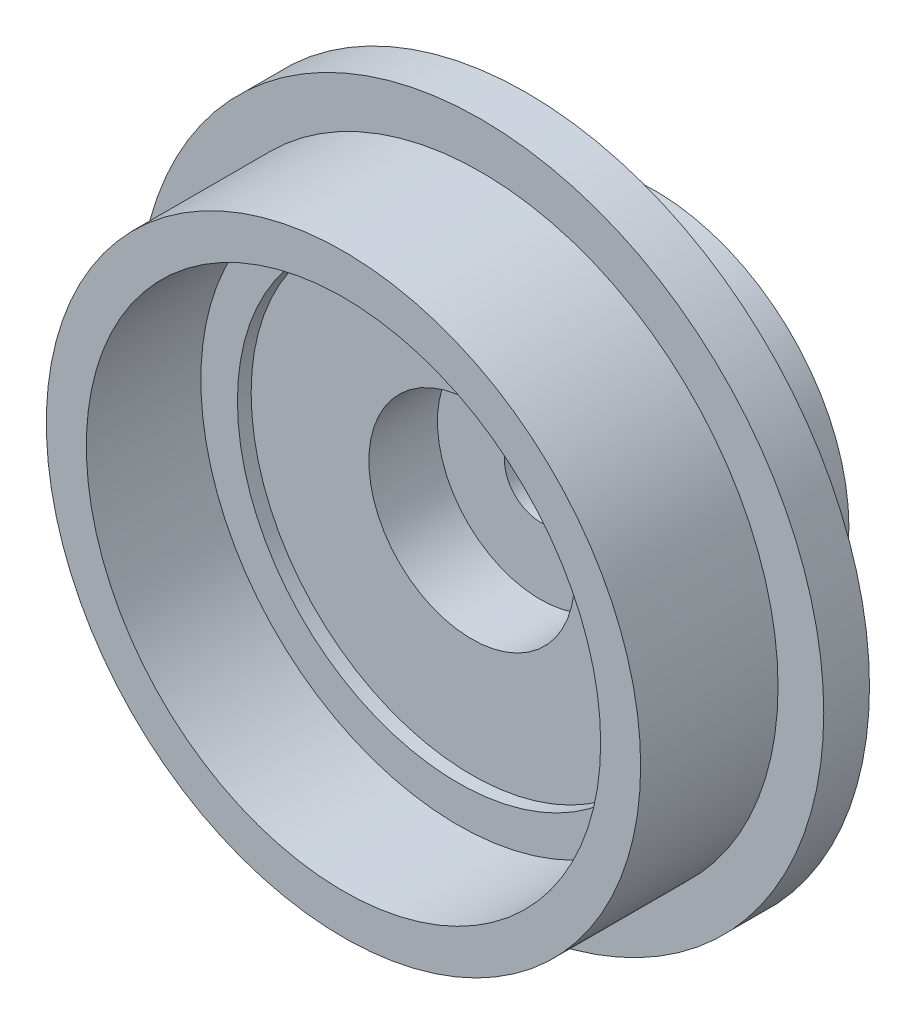
SolidWorks part; units mm, degrees
material "6061-T6 (SS)"
ref_plane "Front Plane" through (0, 0, 0) normal (0, 0, 1) x (1, 0, 0)
ref_plane "Top Plane" through (0, 0, 0) normal (0, 1, 0) x (1, 0, 0)
ref_plane "Right Plane" through (0, 0, 0) normal (1, 0, 0) x (0, 0, -1)
sketch "Sketch1" plane through (0, 0, 0) normal (1, 0, 0) x (0, 0, -1)
  line L0 (-32.3517, 0) -> (72.8588, 0) construction
  line L1 (17.2847, 0) -> (7.1247, 0)
  line L2 (7.1247, 0) -> (7.1247, 12.2555)
  line L3 (7.1247, 12.2555) -> (6.3627, 12.2555)
  line L4 (6.3627, 12.2555) -> (6.3627, 14.2875)
  line L5 (6.3627, 14.2875) -> (0, 14.2875)
  line L6 (0, 14.2875) -> (0, 16.51)
  line L7 (0, 16.51) -> (7.6327, 16.51)
  line L8 (10.1727, 19.05) -> (10.1727, 10.795)
  line L9 (10.1727, 10.795) -> (17.2847, 10.795)
  line L10 (17.2847, 10.795) -> (17.2847, 0)
  line L11 (7.6327, 16.51) -> (7.6327, 19.05)
  line L12 (7.6327, 19.05) -> (10.1727, 19.05)
  dimension "D1" = 28.575
  dimension "D2" = 33.02
  dimension "D3" = 6.3627
  dimension "D4" = 2.032
  dimension "D5" = 0.762
  dimension "D6" = 3.81
  dimension "D7" = 21.59
  dimension "D8" = 7.112
  dimension "D9" = 38.1
  dimension "D10" = 2.54
revolve "Revolve1" add sketch "Sketch1" angle 360 about L0
sketch "Sketch2" plane through (0, 0, -7.1247) normal (0, 0, 1) x (1, 0, 0)
  circle A0 centre (0, 0) radius 1.9939
  dimension "D1" = 3.9878
extrude "Cut-Extrude1" cut sketch "Sketch2" against normal through all
sketch "Sketch3" plane through (0, 0, -7.1247) normal (0, 0, 1) x (1, 0, 0)
  circle A0 centre (0, 0) radius 5.715
  dimension "D1" = 11.43
extrude "Cut-Extrude2" cut sketch "Sketch3" against normal blind 3.81
